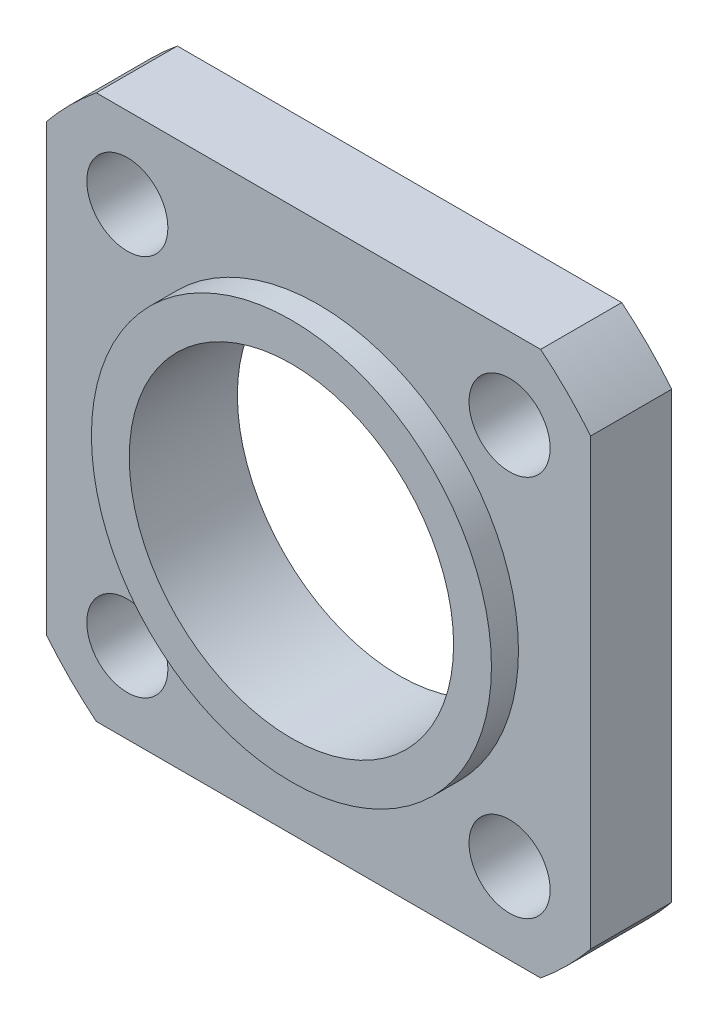
SolidWorks part; units mm, degrees
ref_plane "前视基准面" through (0, 0, 0) normal (0, 0, 1) x (1, 0, 0)
ref_plane "上视基准面" through (0, 0, 0) normal (0, 1, 0) x (1, 0, 0)
ref_plane "右视基准面" through (0, 0, 0) normal (1, 0, 0) x (0, 0, -1)
other "Configuration Table"
sketch "草图1" plane through (0, 0, 0) normal (0, 0, 1) x (1, 0, 0)
  line L0 (-7.0711, 7.0711) -> (0, 0) construction
  line L1 (0, 0) -> (-10, 0) construction
  circle A0 centre (0, 0) radius 10 construction
  circle A1 centre (0, 0) radius 13
  circle A2 centre (0, 0) radius 6
  circle A3 centre (-7.0711, 7.0711) radius 1.5
  circle A4 centre (7.0711, 7.0711) radius 1.5
  circle A5 centre (7.0711, -7.0711) radius 1.5
  circle A6 centre (-7.0711, -7.0711) radius 1.5
  point P7 (6.3738, 4.9804)
  point P9 (0, 0)
  point P17 (0, 0)
  dimension "D1" = 20
  dimension "D2" = 26
  dimension "D3" = 12
  dimension "D5" = 3
  dimension "D4" = 45
  dimension "D6" = 4
extrude "凸台-拉伸1" add sketch "草图1" along normal blind 3
sketch "草图2" plane through (0, 0, 3) normal (0, 0, 1) x (1, 0, 0)
  circle A0 centre (0, 0) radius 7.4
  circle A1 centre (0, 0) radius 6
  dimension "D1" = 14.8
  dimension "D2" = 12
extrude "凸台-拉伸2" add sketch "草图2" along normal blind 1
sketch "草图3" plane through (0, 0, 3) normal (0, 0, 1) x (1, 0, 0)
  line L0 (-8.2203, 10.0711) -> (8.2203, 10.0711)
  line L1 (10.0711, 8.2203) -> (10.0711, -8.2203)
  line L2 (8.2203, -10.0711) -> (-8.2203, -10.0711)
  line L3 (-10.0711, -8.2203) -> (-10.0711, 8.2203)
  circle A0 centre (0, 0) radius 13 construction
  circle A1 centre (-7.0711, 7.0711) radius 1.5 construction
  arc A2 (-10.0711, 8.2203) -> (-10.0711, -8.2203) centre (0, 0) ccw
  arc A3 (8.2203, 10.0711) -> (-8.2203, 10.0711) centre (0, 0) ccw
  arc A4 (10.0711, -8.2203) -> (10.0711, 8.2203) centre (0, 0) ccw
  arc A5 (-8.2203, -10.0711) -> (8.2203, -10.0711) centre (0, 0) ccw
  point P7 (0, 0)
  point P16 (0, 0)
  dimension "D1" = 3
  dimension "D2" = 4
extrude "切除-拉伸1" cut sketch "草图3" against normal blind 41
